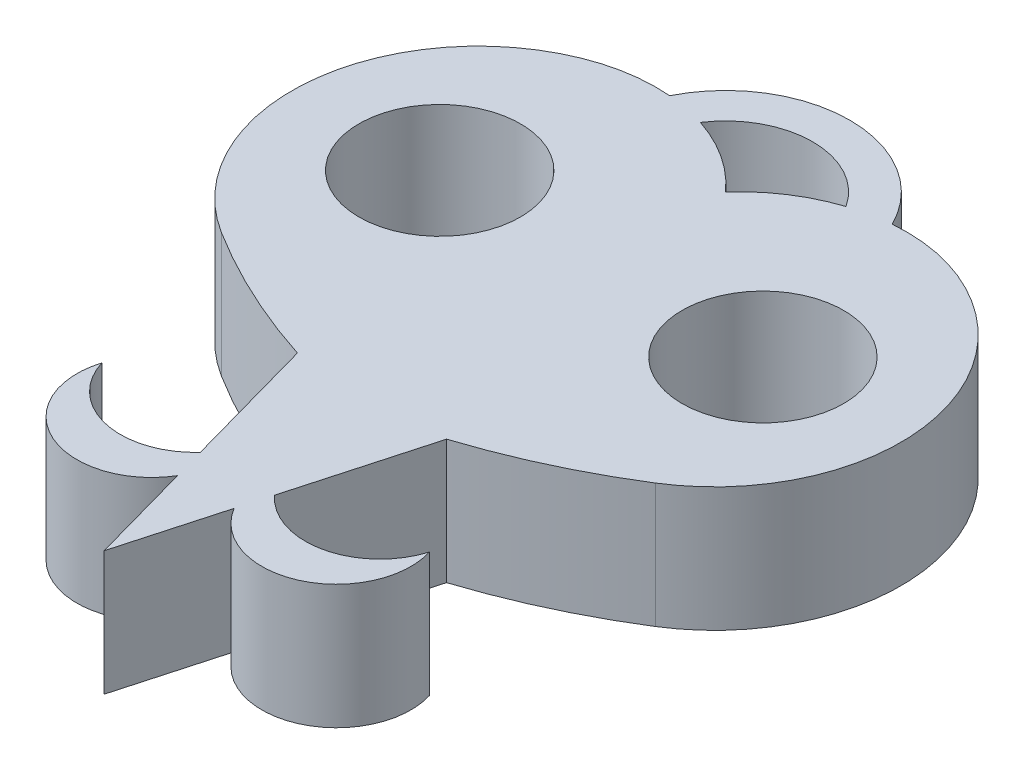
SolidWorks part; units mm, degrees
ref_plane "前视基准面" through (0, 0, 0) normal (0, 0, 1) x (1, 0, 0)
ref_plane "上视基准面" through (0, 0, 0) normal (0, 1, 0) x (1, 0, 0)
ref_plane "右视基准面" through (0, 0, 0) normal (1, 0, 0) x (0, 0, -1)
sketch "草图1" plane through (0, 0, 0) normal (0, 1, 0) x (1, 0, 0)
  line L0 (0, 0) -> (0, 30) construction
  line L1 (0, 0) -> (0, -20) construction
  line L2 (0, -20) -> (6, 1.5516)
  line L3 (0, -20) -> (-6, 1.5516)
  arc A0 (0, 30) -> (15.1231, 33.5155) centre (10.0623, 21) cw
  arc A1 (15.1231, 33.5155) -> (17.4606, 6.896) centre (9.5, 19.6094) cw
  arc A2 (17.4606, 6.896) -> (0, 0) centre (-9.8707, 50.5452) cw construction
  arc A3 (6, 1.5516) -> (17.4606, 6.896) centre (-9.8707, 50.5452) ccw
  arc A6 (1.7, -7) -> (13.1782, -7) centre (7.4391, -8.75) ccw
  arc A7 (1.7, -7) -> (13.1782, -7) centre (7.4391, -5.25) ccw
  circle A8 centre (13, 20) radius 6.5
  circle A9 centre (-13, 20) radius 6.5
  arc A10 (-1.7, -7) -> (-13.1782, -7) centre (-7.4391, -5.25) cw
  arc A11 (-1.7, -7) -> (-13.1782, -7) centre (-7.4391, -8.75) cw
  arc A12 (-6, 1.5516) -> (-17.4606, 6.896) centre (9.8707, 50.5452) cw
  arc A13 (-15.1231, 33.5155) -> (-17.4606, 6.896) centre (-9.5, 19.6094) ccw
  arc A14 (0, 30) -> (-15.1231, 33.5155) centre (-10.0623, 21) ccw
  arc A15 (-5.8598, 33.8292) -> (5.8598, 33.8292) centre (0, 30) cw
  arc A16 (-8.9531, 34.4544) -> (8.9531, 34.4544) centre (0, 30) cw
  point P35 (0, 0)
  dimension "D3" = 13.5
  dimension "D4" = 15
  dimension "D5" = 51.5
  dimension "D9" = 6
  dimension "D10" = 6
  dimension "D14" = 13
  dimension "D17" = 7
  dimension "D18" = 10
  dimension "D1" = 30
  dimension "D2" = 20
  dimension "D6" = 6
  dimension "D7" = 9
  dimension "D8" = 9.5
  dimension "D11" = 3.5
  dimension "D12" = 1.7
  dimension "D13" = 13
  dimension "D15" = 13
  dimension "D16" = 10
extrude "凸台-拉伸3" add sketch "草图1" along normal blind 10 contours A16 A14 A15 A0 | A0 A14 A13 A12 L3 A10 A11 L2 A6 A7 A3 A1 A9 A8 | A7 A6 L2 | A7 L2 A6 | A11 A10 L3 | A11 L3 A10
scale "缩放比例1" scale about centroid uniform scaling yes scale factor 1.4
